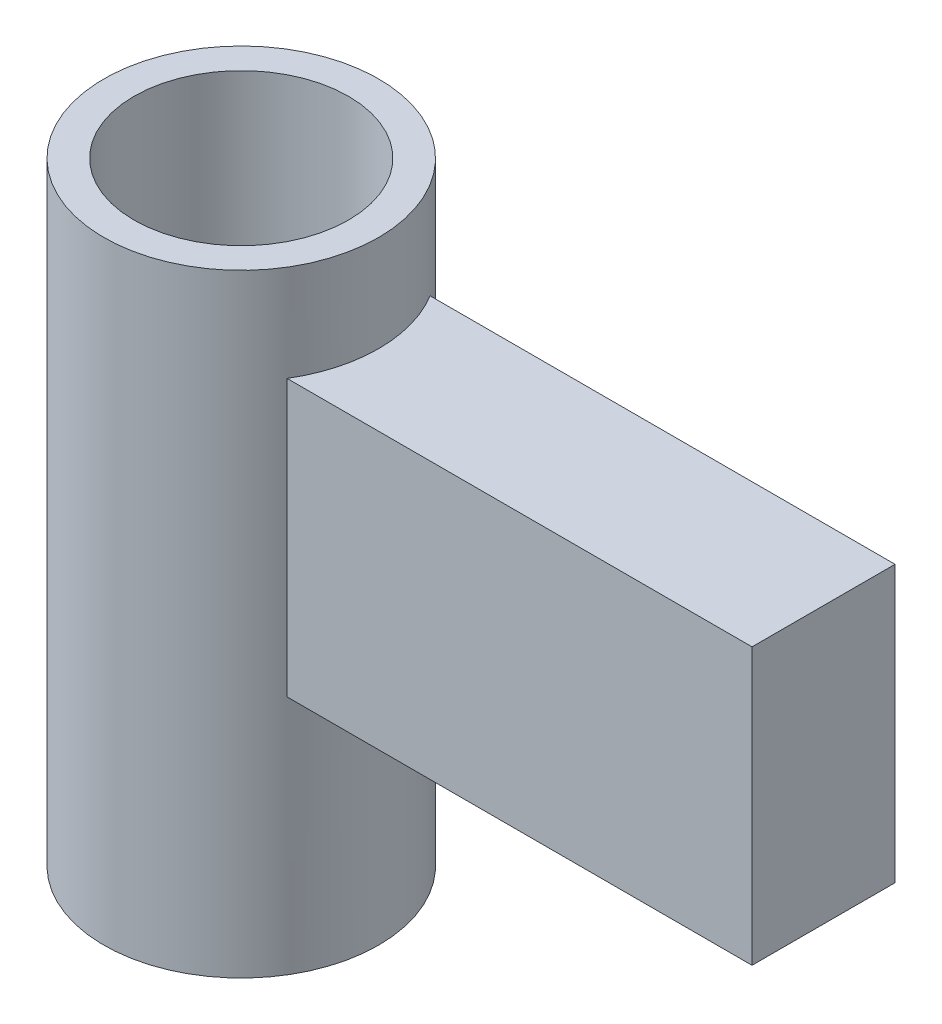
SolidWorks part; units mm, degrees
ref_plane "前基準面" through (0, 0, 0) normal (0, 0, 1) x (1, 0, 0)
ref_plane "上基準面" through (0, 0, 0) normal (0, 1, 0) x (1, 0, 0)
ref_plane "右基準面" through (0, 0, 0) normal (1, 0, 0) x (0, 0, -1)
sketch "草圖1" plane through (0, 0, 0) normal (0, 1, 0) x (1, 0, 0)
  circle A0 centre (0, 0) radius 10.5
  dimension "D1" = 21
extrude "伸長-薄件1" add sketch "草圖1" along normal blind 60 thin
ref_plane "平面1" through (10, 0, 0) normal (1, 0, 0) x (0, 0, -1)
sketch "草圖2" plane through (10, 0, 0) normal (1, 0, 0) x (0, 0, -1)
  line L0 (0, -1000) -> (0, 49000) construction
  line L2 (-7, 50.5713) -> (7, 50.5713)
  line L3 (-7, 50.5713) -> (-7, 23.5713)
  line L4 (-7, 23.5713) -> (7, 23.5713)
  line L5 (7, 50.5713) -> (7, 23.5713)
  line L6 (-7, 50.5713) -> (7, 23.5713) construction
  line L7 (-7, 23.5713) -> (7, 50.5713) construction
  point P1 (0, 37.0713)
  dimension "D1" = 27
  dimension "D2" = 14
extrude "填料-伸長1" add sketch "草圖2" along normal blind 47 and the other way blind 5
